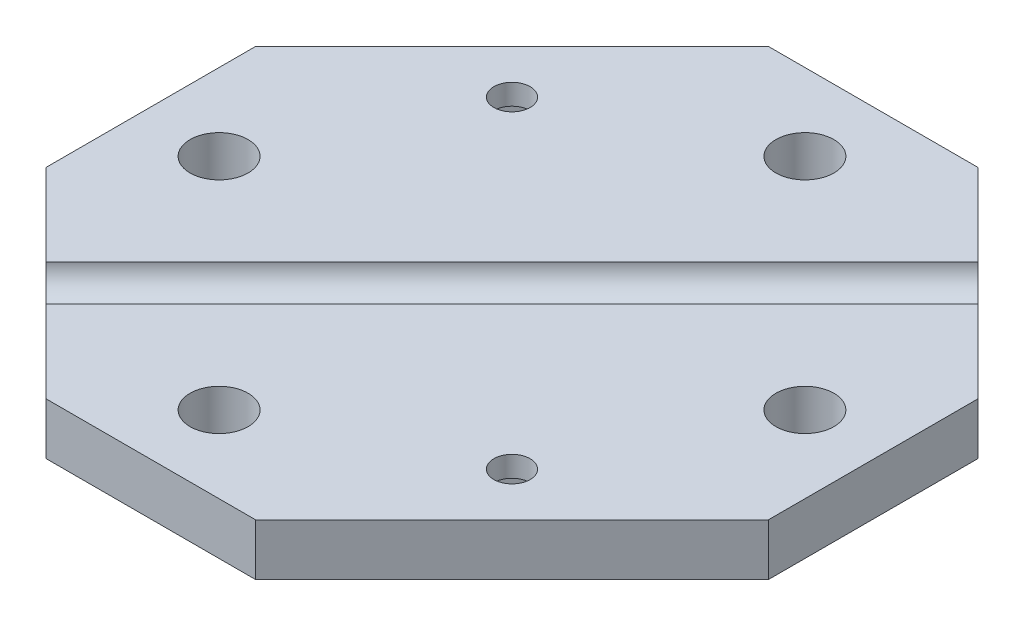
SolidWorks part; units mm, degrees
ref_plane "Front Plane" through (0, 0, 0) normal (0, 0, 1) x (1, 0, 0)
ref_plane "Top Plane" through (0, 0, 0) normal (0, 1, 0) x (1, 0, 0)
ref_plane "Right Plane" through (0, 0, 0) normal (1, 0, 0) x (0, 0, -1)
sketch "Sketch1" plane through (0, 0, 0) normal (0, 1, 0) x (1, 0, 0)
  line L0 (-40.3039, 15.5552) -> (-15.5552, 40.3039)
  line L1 (-40.3039, -40.3039) -> (40.3039, -40.3039) construction
  line L2 (-40.3039, -40.3039) -> (-40.3039, 40.3039) construction
  line L3 (-40.3039, 40.3039) -> (40.3039, 40.3039) construction
  line L4 (40.3039, -40.3039) -> (40.3039, 40.3039) construction
  line L5 (-40.3039, -40.3039) -> (40.3039, 40.3039) construction
  line L6 (-40.3039, 40.3039) -> (40.3039, -40.3039) construction
  line L7 (-27.9296, 27.9296) -> (2.476, -2.476) construction
  line L8 (-11.6661, -16.6182) -> (16.6182, 11.6661) construction
  line L9 (-11.6661, -16.6182) -> (-32.8793, 4.5951) construction
  line L10 (16.6182, 11.6661) -> (-4.5951, 32.8793) construction
  line L11 (-40.3039, 15.5552) -> (-40.3039, -4.6948)
  line L12 (-15.5552, 40.3039) -> (4.6948, 40.3039)
  line L13 (24.0428, 0.706) -> (24.0428, 20.956)
  line L14 (-0.706, -24.0428) -> (-20.956, -24.0428)
  line L15 (-32.8793, 4.5951) -> (-4.5951, 32.8793) construction
  line L16 (-18.7372, 18.7372) -> (11.6684, -11.6684) construction
  line L17 (-0.706, -24.0428) -> (24.0428, 0.706)
  line L18 (-40.3039, -4.6948) -> (-20.956, -24.0428)
  line L19 (4.6948, 40.3039) -> (24.0428, 20.956)
  circle A0 centre (-11.6661, -16.6182) radius 2.8
  circle A1 centre (16.6182, 11.6661) radius 2.8
  circle A2 centre (-4.5951, 32.8793) radius 2.8
  circle A3 centre (-32.8793, 4.5951) radius 2.8
  point P0 (0, 0)
  point P13 (2.476, -2.476)
  point P28 (11.6684, -11.6684)
  dimension "D6" = 5.6
  dimension "D1" = 135
  dimension "D2" = 35
  dimension "D3" = 43
  dimension "D4" = 40
  dimension "D5" = 30
  dimension "D7" = 20.25
  dimension "D8" = 20.25
  dimension "D9" = 43
  dimension "D10" = 35
  dimension "D11" = 20.25
  dimension "D12" = 20.25
extrude "Boss-Extrude1" add sketch "Sketch1" along normal blind 5
sketch "Sketch2" plane through (0, 5, 0) normal (0, 1, 0) x (1, 0, 0)
  line L0 (-27.9296, 27.9296) -> (11.6684, -11.6684) construction
  line L1 (-15.5552, 40.3039) -> (-40.3039, 15.5552) construction
  line L2 (-0.706, -24.0428) -> (24.0428, 0.706) construction
  line L3 (-18.7372, -2.476) -> (2.476, 18.7372) construction
  line L4 (-12.55, 33.7632) -> (17.502, 3.7112) construction
  line L5 (-12.55, 33.7632) -> (-33.7632, 12.55) construction
  line L6 (-33.7632, 12.55) -> (-3.7112, -17.502) construction
  line L7 (-3.7112, -17.502) -> (17.502, 3.7112) construction
  line L8 (15.7343, 5.4789) -> (13.9665, 3.7112) construction
  line L9 (13.9665, 3.7112) -> (15.7343, 1.9434) construction
  line L10 (-5.4789, -15.7343) -> (-3.7112, -13.9665) construction
  line L11 (-3.7112, -13.9665) -> (-1.9434, -15.7343) construction
  line L12 (-23.1566, 23.1566) -> (-21.3181, 21.3181) construction
  circle A0 centre (13.9665, 3.7112) radius 1.75
  circle A1 centre (-3.7112, -13.9665) radius 1.75
  circle A3 centre (-21.3181, 21.3181) radius 1.75
  point P9 (-8.1306, 8.1306)
  point P12 (2.476, 18.7372)
  dimension "D7" = 3.5
  dimension "D10" = 3.5
  dimension "D11" = 2.6
  dimension "D12" = 3.5
  dimension "D1" = 30
  dimension "D2" = 42.5
  dimension "D3" = 30
  dimension "D4" = 42.5
  dimension "D5" = 2.5
  dimension "D6" = 2.5
  dimension "D8" = 2.5
  dimension "D9" = 2.5
sketch "Sketch3" plane through (0, 5, 0) normal (0, 1, 0) x (1, 0, 0)
  line L0 (-30.63, -14.3688) -> (14.3688, 30.63) construction
  line L1 (-40.3039, -4.6948) -> (-20.956, -24.0428) construction
  line L2 (24.0428, 20.956) -> (4.6948, 40.3039) construction
sketch "Sketch4" plane through (22.4994, 0, -22.4994) normal (0.7071, 0, -0.7071) x (-0.7071, 0, -0.7071)
  line L0 (13.9984, 5) -> (8.9984, 5)
  line L1 (-2.1827, 5) -> (25.1795, 5) construction
  arc A0 (8.9984, 5) -> (13.9984, 5) centre (11.4984, 5) ccw
  point P5 (11.4984, 5)
  dimension "D1" = 5
extrude "Cut-Extrude1" cut sketch "Sketch4" against normal up to next
sketch "Sketch5" plane through (0, 5, 0) normal (0, 1, 0) x (1, 0, 0)
  line L0 (11.6684, -11.6684) -> (-6.3628, 6.3628) construction
  line L1 (-0.706, -24.0428) -> (24.0428, 0.706) construction
  line L2 (-28.8622, -16.1366) -> (16.1366, 28.8622) construction
  line L3 (-9.8984, 9.8984) -> (-27.9296, 27.9296) construction
  line L4 (-32.3977, -12.601) -> (12.601, 32.3977) construction
  line L5 (-15.5552, 40.3039) -> (-40.3039, 15.5552) construction
  line L7 (-21.3599, 26.0139) -> (-24.5387, 26.8657)
  line L8 (-24.5387, 26.8657) -> (-26.8657, 24.5387)
  line L9 (-26.8657, 24.5387) -> (-26.0139, 21.3599)
  line L10 (-26.0139, 21.3599) -> (-22.8352, 20.5082)
  line L11 (-22.8352, 20.5082) -> (-20.5082, 22.8352)
  line L12 (-20.5082, 22.8352) -> (-21.3599, 26.0139)
  line L13 (9.7528, -5.0987) -> (6.574, -4.247)
  line L14 (6.574, -4.247) -> (4.247, -6.574)
  line L15 (4.247, -6.574) -> (5.0987, -9.7528)
  line L16 (5.0987, -9.7528) -> (8.2775, -10.6045)
  line L17 (8.2775, -10.6045) -> (10.6045, -8.2775)
  line L18 (10.6045, -8.2775) -> (9.7528, -5.0987)
  circle A0 centre (-23.6869, 23.6869) radius 2.85 construction
  circle A1 centre (7.4258, -7.4258) radius 2.85 construction
  point P21 (0, 0)
  point P29 (0, 0)
  point P30 (0, 0)
  point P31 (0, 0)
  point P32 (0, 0)
  dimension "D1" = 5.7
  dimension "D2" = 5.7
  dimension "D3" = 6
  dimension "D4" = 6
extrude "Cut-Extrude2" cut sketch "Sketch5" against normal blind 3 from offset 2 offset against normal yes
sketch "Sketch6" plane through (0, 5, 0) normal (0, 1, 0) x (1, 0, 0)
  line L0 (-9.8984, 9.8984) -> (-27.9296, 27.9296) construction
  line L1 (-32.3977, -12.601) -> (12.601, 32.3977) construction
  line L2 (-15.5552, 40.3039) -> (-40.3039, 15.5552) construction
  line L3 (-6.3628, 6.3628) -> (11.6684, -11.6684) construction
  line L4 (-28.8622, -16.1366) -> (16.1366, 28.8622) construction
  line L5 (-0.706, -24.0428) -> (24.0428, 0.706) construction
  circle A0 centre (-23.6869, 23.6869) radius 1.75
  circle A1 centre (7.4258, -7.4258) radius 1.75
  point P16 (0, 0)
  point P17 (0, 0)
  point P18 (0, 0)
  point P19 (0, 0)
  dimension "D1" = 3.5
  dimension "D2" = 6
  dimension "D3" = 6
extrude "Cut-Extrude3" cut sketch "Sketch6" against normal up to next
